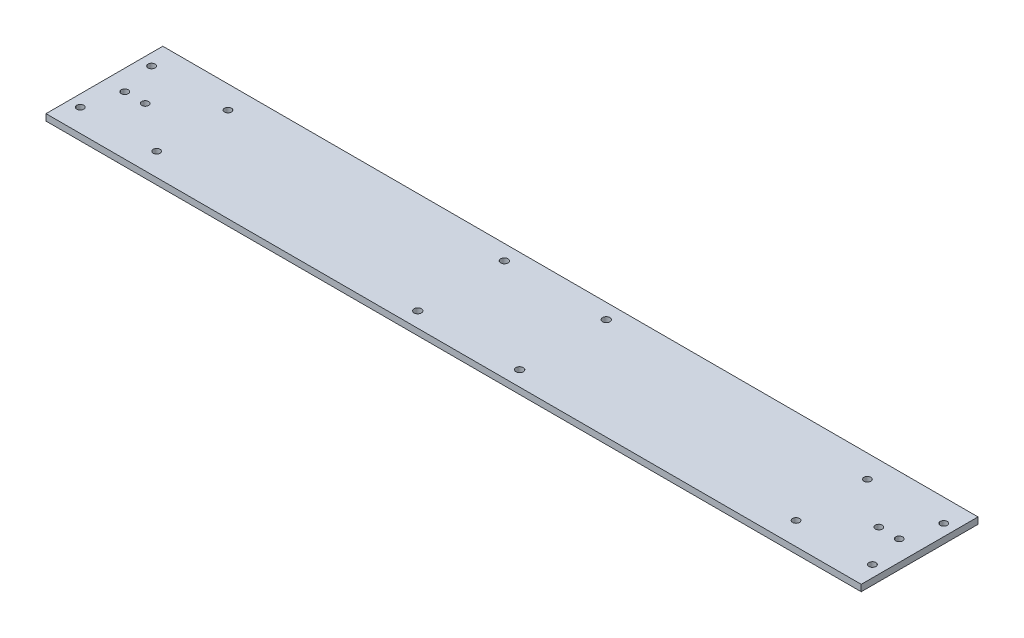
SolidWorks part; units mm, degrees
material "Acrylic (Medium-high impact)"
ref_plane "Front Plane" through (0, 0, 0) normal (0, 0, 1) x (1, 0, 0)
ref_plane "Top Plane" through (0, 0, 0) normal (0, 1, 0) x (1, 0, 0)
ref_plane "Right Plane" through (0, 0, 0) normal (1, 0, 0) x (0, 0, -1)
sketch "Sketch1" plane through (0, 0, 0) normal (0, 1, 0) x (1, 0, 0)
  line L1 (-200, 28.65) -> (200, 28.65)
  line L2 (-200, 28.65) -> (-200, -28.65)
  line L3 (-200, -28.65) -> (200, -28.65)
  line L4 (200, 28.65) -> (200, -28.65)
  line L5 (-200, 28.65) -> (200, -28.65) construction
  line L6 (-200, -28.65) -> (200, 28.65) construction
  point P0 (0, 0)
  dimension "D1" = 400
  dimension "D2" = 57.3
extrude "Boss-Extrude1" add sketch "Sketch1" along normal blind 3.175
sketch "Sketch2" plane through (0, 3.175, 0) normal (0, 1, 0) x (1, 0, 0)
  circle A0 centre (-194.3382, -17.5) radius 1.7 construction
  circle A1 centre (-194.3382, 17.5) radius 1.7 construction
  circle A2 centre (-190, 0) radius 1.7 construction
  circle A3 centre (-180, 0) radius 1.7 construction
  circle A4 centre (-156.8618, -17.5) radius 1.7 construction
  circle A5 centre (-156.8618, 17.5) radius 1.7 construction
  circle A6 centre (156.8618, 17.5) radius 1.7 construction
  circle A7 centre (156.8618, -17.5) radius 1.7 construction
  circle A8 centre (194.3382, -17.5) radius 1.7 construction
  circle A9 centre (180, 0) radius 1.7 construction
  circle A10 centre (190, 0) radius 1.7 construction
  circle A11 centre (194.3382, 17.5) radius 1.7 construction
  circle A12 centre (-194.3382, -17.5) radius 1.7
  circle A13 centre (-194.3382, 17.5) radius 1.7
  circle A14 centre (-190, 0) radius 1.7
  circle A15 centre (-180, 0) radius 1.7
  circle A16 centre (-156.8618, -17.5) radius 1.7
  circle A17 centre (-156.8618, 17.5) radius 1.7
  circle A18 centre (156.8618, 17.5) radius 1.7
  circle A19 centre (156.8618, -17.5) radius 1.7
  circle A20 centre (194.3382, -17.5) radius 1.7
  circle A21 centre (180, 0) radius 1.7
  circle A22 centre (190, 0) radius 1.7
  circle A23 centre (194.3382, 17.5) radius 1.7
extrude "Cut-Extrude1" cut sketch "Sketch2" against normal through all
hole_wizard "M3 Clearance Hole1" positions "Sketch3" profile "Sketch4" hole size "M3" standard "ANSI Metric"
sketch "Sketch3" plane through (0, 3.175, 0) normal (0, 1, 0) x (1, 0, 0)
  line L1 (-25, 21.25) -> (25, 21.25)
  line L2 (-25, 21.25) -> (-25, -21.25)
  line L3 (-25, -21.25) -> (25, -21.25)
  line L4 (25, 21.25) -> (25, -21.25)
  line L5 (-25, 21.25) -> (25, -21.25) construction
  line L6 (-25, -21.25) -> (25, 21.25) construction
  point P2 (25, -21.25)
  point P27 (-25, 21.25)
  point P28 (-25, -21.25)
  point P29 (25, 21.25)
  point P32 (0, 0)
  dimension "D1" = 42.5
  dimension "D2" = 50
sketch "Sketch4" plane through (25, 3.175, 21.25) normal (1, 0, 0) x (0, 0, 1)
  line L0 (0, 0) -> (0, 5)
  line L1 (0, 5) -> (1.8, 3.9185)
  line L2 (1.8, 3.9185) -> (1.8, 0)
  line L5 (1.8, 0) -> (0, 0)
  line L10 (0, 5) -> (-1.8, 3.9185) construction
  line L11 (0, -6.35) -> (0, 107.95) construction
  dimension "Hole Dia." = 3.6
  dimension "Hole Depth" = 5
  dimension "Drill Angle" = 118
